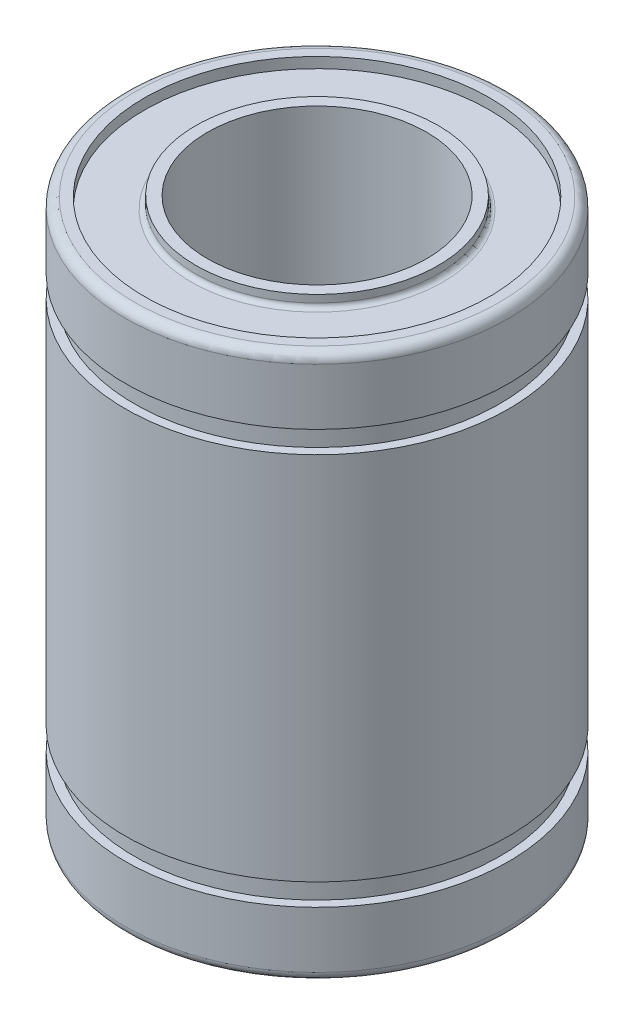
SolidWorks part; units mm, degrees
ref_plane "Front Plane" through (0, 0, 0) normal (0, 0, 1) x (1, 0, 0)
ref_plane "Top Plane" through (0, 0, 0) normal (0, 1, 0) x (1, 0, 0)
ref_plane "Right Plane" through (0, 0, 0) normal (1, 0, 0) x (0, 0, -1)
sketch "Sketch1" plane through (0, 0, 0) normal (0, 0, 1) x (1, 0, 0)
  line L0 (6.635, 15.0004) -> (6, 15.0004)
  line L1 (6, 15.0004) -> (6, -15.0004)
  line L2 (6, -15.0004) -> (6.635, -15.0004)
  line L3 (6.635, -15.0004) -> (6.635, -14.594)
  line L4 (6.889, -14.34) -> (9.435, -14.34)
  line L5 (9.435, -14.34) -> (9.435, -14.92)
  line L6 (9.435, -14.92) -> (9.977, -14.92)
  line L7 (10.485, -14.412) -> (10.485, -11.325)
  line L8 (10.485, -11.325) -> (10, -11.325)
  line L9 (10, -11.325) -> (10, -10.125)
  line L10 (10, -10.125) -> (10.485, -10.125)
  line L11 (10.485, -10.125) -> (10.485, 10.125)
  line L12 (10.485, 10.125) -> (10, 10.125)
  line L13 (10, 10.125) -> (10, 11.325)
  line L14 (10, 11.325) -> (10.485, 11.325)
  line L15 (10.485, 11.325) -> (10.485, 14.412)
  line L16 (9.977, 14.92) -> (9.435, 14.92)
  line L17 (9.435, 14.92) -> (9.435, 14.34)
  line L18 (9.435, 14.34) -> (6.889, 14.34)
  line L19 (6.635, 14.594) -> (6.635, 15.0004)
  line L20 (0, 15.0004) -> (0, -15.0004) construction
  arc A0 (6.635, -14.594) -> (6.889, -14.34) centre (6.889, -14.594) cw
  arc A1 (9.977, -14.92) -> (10.485, -14.412) centre (9.977, -14.412) ccw
  arc A2 (10.485, 14.412) -> (9.977, 14.92) centre (9.977, 14.412) ccw
  arc A3 (6.889, 14.34) -> (6.635, 14.594) centre (6.889, 14.594) cw
revolve "Revolve1" add sketch "Sketch1" angle 360 about L20
